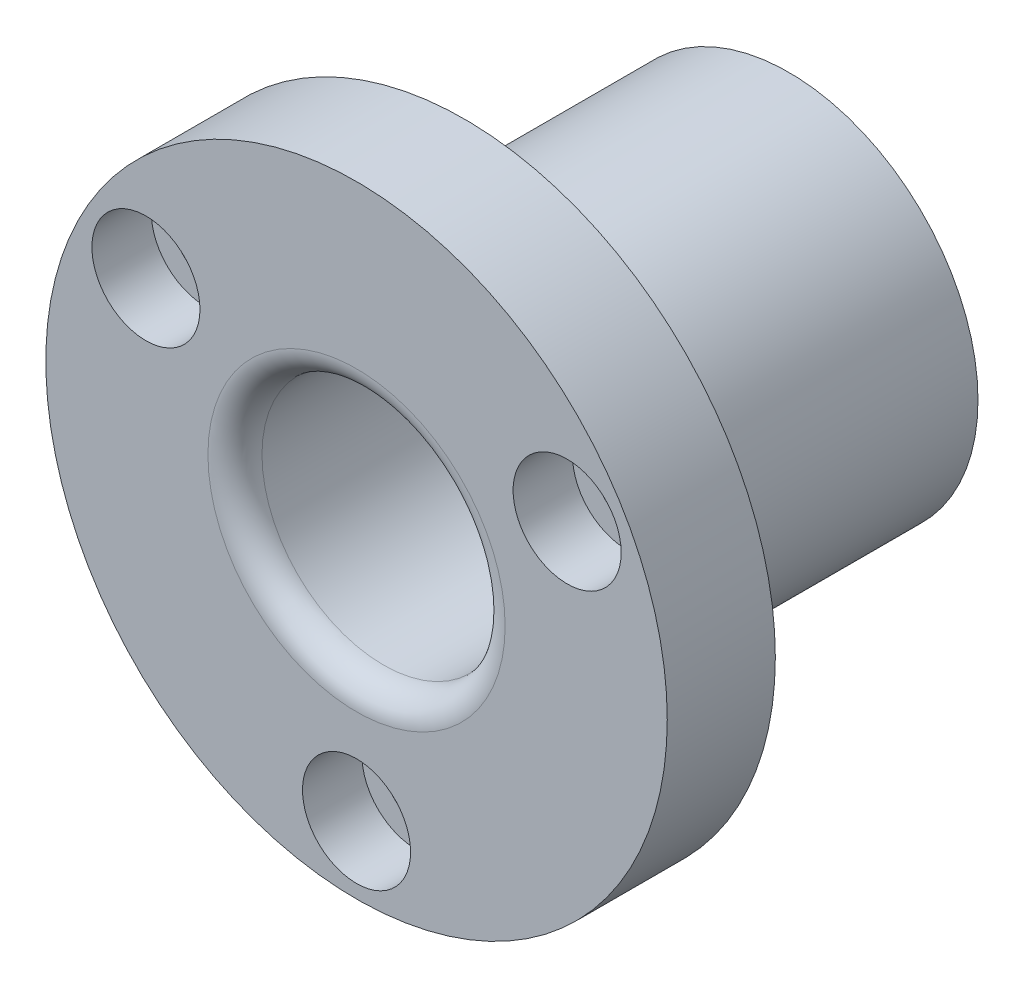
SolidWorks part; units mm, degrees
ref_plane "Front Plane" through (0, 0, 0) normal (0, 0, 1) x (1, 0, 0)
ref_plane "Top Plane" through (0, 0, 0) normal (0, 1, 0) x (1, 0, 0)
ref_plane "Right Plane" through (0, 0, 0) normal (1, 0, 0) x (0, 0, -1)
sketch "Sketch1" plane through (0, 0, 0) normal (0, 0, 1) x (1, 0, 0)
  circle A0 centre (0, 0) radius 14
  dimension "D1" = 28
extrude "Boss-Extrude1" add sketch "Sketch1" along normal blind 24
sketch "Sketch2" plane through (0, 0, 24) normal (0, 0, 1) x (1, 0, 0)
  circle A0 centre (0, 0) radius 23
  circle A1 centre (0, 0) radius 18 construction
  circle A2 centre (0, 0) radius 9
  dimension "D1" = 46
  dimension "D2" = 36
  dimension "D3" = 18
extrude "Boss-Extrude2" add sketch "Sketch2" along normal blind 8
sketch "Sketch3" plane through (0, 0, 24) normal (0, 0, 1) x (1, 0, 0)
  circle A0 centre (0, 0) radius 9
extrude "Cut-Extrude1" cut sketch "Sketch3" against normal through all
hole_wizard "CBORE for M4 Hex Socket Head Cap Screw1" positions "Sketch4" profile "Sketch6" counterbore size "M4" standard "ISO" end condition through all
sketch "Sketch4" plane through (0, 0, 32) normal (0, 0, 1) x (1, 0, 0)
  circle A0 centre (0, 0) radius 18 construction
  point P0 (0, -18)
  dimension "D1" = 36
sketch "Sketch6" plane through (0, -18, 32) normal (1, 0, 0) x (0, -1, 0)
  line L0 (0, 0) -> (0, 32)
  line L1 (0, 32) -> (2.25, 32)
  line L3 (2.25, 32) -> (2.25, 4.4)
  line L4 (2.25, 4.4) -> (4, 4.4)
  line L5 (4, 4.4) -> (4, 0)
  line L7 (4, 0) -> (0, 0)
  line L11 (0, -6.35) -> (0, 107.95) construction
  dimension "Thru Hole Dia." = 4.5
  dimension "Thru Hole Depth" = 32
  dimension "C'Bore Dia." = 8
  dimension "C'Bore Depth" = 4.4
pattern_circular "CirPattern1" count 3 over 360 about axis through (0, 0, 0) along (0, 0, 1) of "CBORE for M4 Hex Socket Head Cap Screw1"
fillet "Fillet1" radius 2 1 edges at (9, 0, 32)
fillet "Fillet2" radius 1 1 edges at (14, 0, 24)
